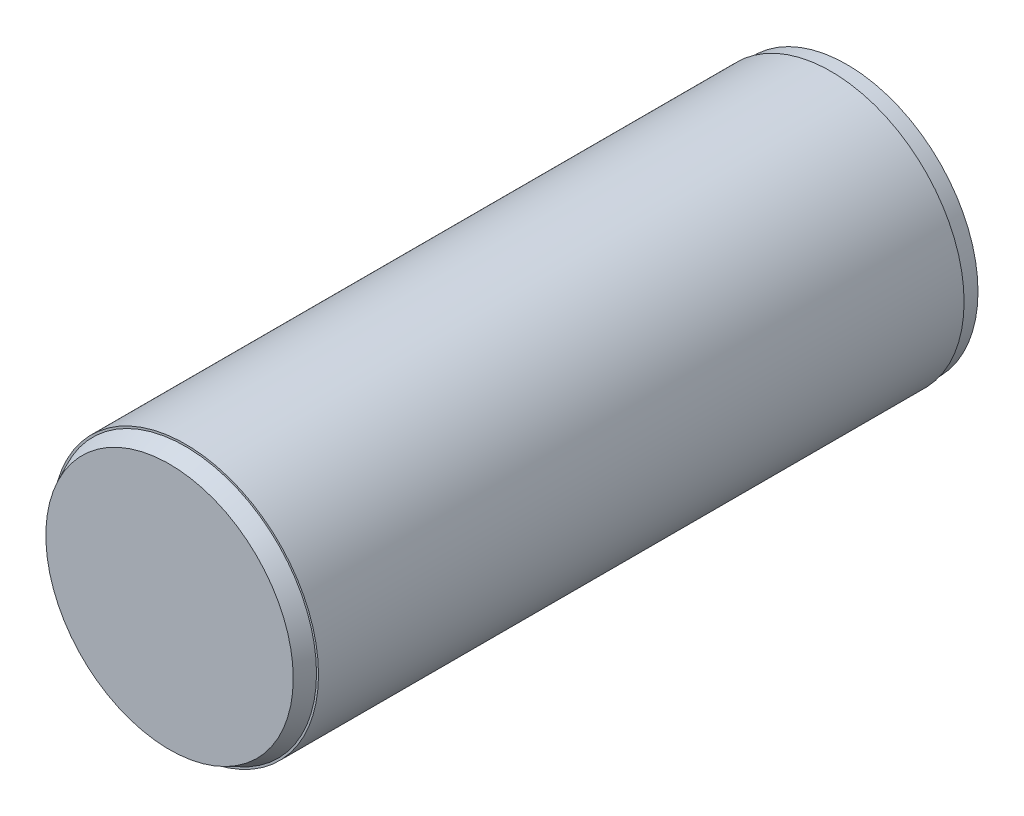
SolidWorks part; units mm, degrees
material "6061-T6 (SS)"
ref_plane "Front Plane" through (0, 0, 0) normal (0, 0, 1) x (1, 0, 0)
ref_plane "Top Plane" through (0, 0, 0) normal (0, 1, 0) x (1, 0, 0)
ref_plane "Right Plane" through (0, 0, 0) normal (1, 0, 0) x (0, 0, -1)
sketch "Sketch1" plane through (0, 0, 0) normal (0, 0, 1) x (1, 0, 0)
  circle A0 centre (0, 0) radius 5105.4
  dimension "D1" = 10210.8
extrude "Boss-Extrude1" add sketch "Sketch1" along normal blind 50.8
sketch "Sketch2" plane through (0, 0, 50.8) normal (0, 0, 1) x (1, 0, 0)
  circle A0 centre (0, 0) radius 5092.7
  circle A1 centre (0, 0) radius 5105.4
  dimension "D1" = 10210.8
  dimension "D2" = 12.7
extrude "Boss-Extrude2" add sketch "Sketch2" along normal blind 24688.8
ref_plane "Plane1" through (0, 0, 24739.6) normal (0, 0, 1) x (1, 0, 0)
sketch "Sketch3" plane through (0, 0, 24739.6) normal (0, 0, 1) x (1, 0, 0)
  circle A0 centre (0, 0) radius 5105.4
extrude "Boss-Extrude3" add sketch "Sketch3" along normal blind 25.4
sketch "Sketch4" plane through (0, 0, 24765) normal (0, 0, 1) x (1, 0, 0)
  circle A0 centre (0, 0) radius 5029.2
  dimension "D1" = 10058.4
extrude "Boss-Extrude4" add sketch "Sketch4" along normal blind 609.6 draft 25
sketch "Sketch5" plane through (0, 0, 0) normal (0, 0, -1) x (-1, 0, 0)
  circle A0 centre (0, 0) radius 5029.2
  circle A1 centre (0, 0) radius 4876.8
  dimension "D1" = 10058.4
  dimension "D2" = 9753.6
extrude "Boss-Extrude5" add sketch "Sketch5" along normal blind 609.6
